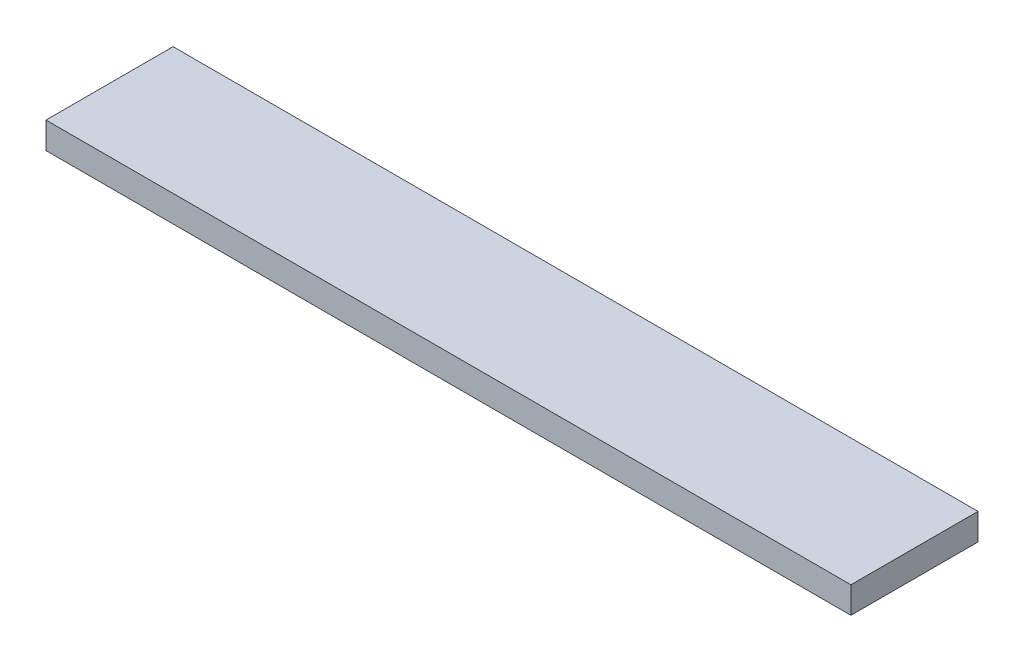
SolidWorks part; units mm, degrees
ref_plane "Front Plane" through (0, 0, 0) normal (0, 0, 1) x (1, 0, 0)
ref_plane "Top Plane" through (0, 0, 0) normal (0, 1, 0) x (1, 0, 0)
ref_plane "Right Plane" through (0, 0, 0) normal (1, 0, 0) x (0, 0, -1)
sketch "Sketch1" plane through (0, 0, 0) normal (0, 1, 0) x (1, 0, 0)
  line L1 (-380, 60) -> (380, 60)
  line L2 (-380, 60) -> (-380, -60)
  line L3 (-380, -60) -> (380, -60)
  line L4 (380, 60) -> (380, -60)
  line L5 (-380, 60) -> (380, -60) construction
  line L6 (-380, -60) -> (380, 60) construction
  point P0 (0, 0)
  dimension "D1" = 120
  dimension "D2" = 760
extrude "Boss-Extrude1" add sketch "Sketch1" along normal blind 25
